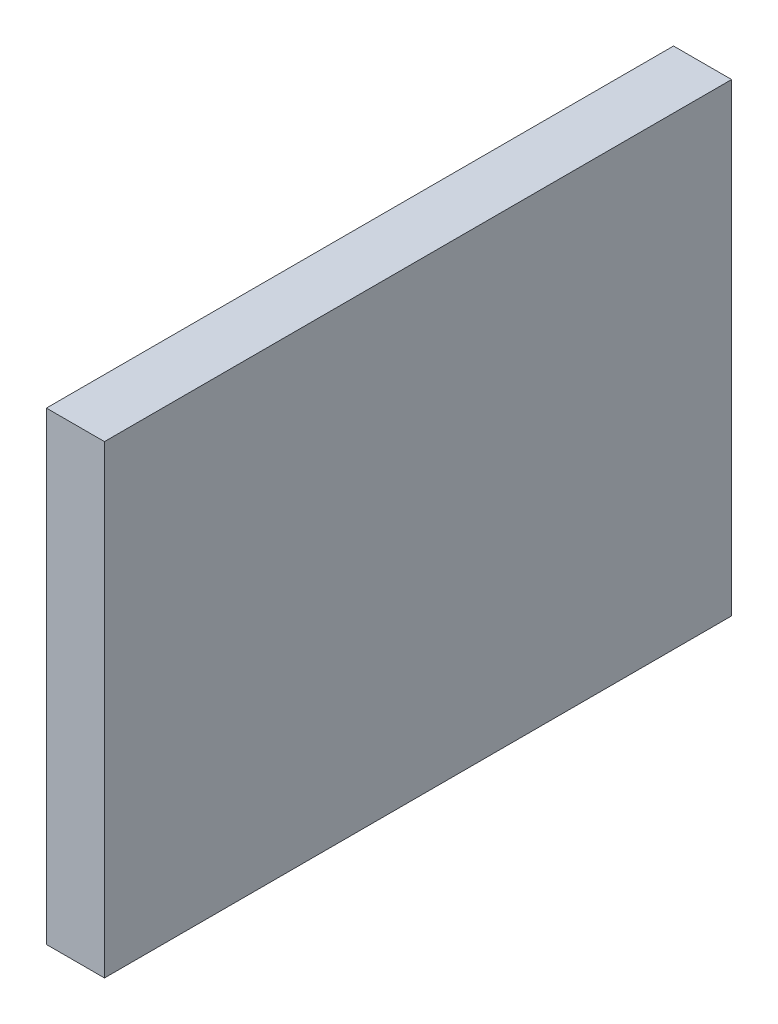
SolidWorks part; units mm, degrees
ref_plane "Front Plane" through (0, 0, 0) normal (0, 0, 1) x (1, 0, 0)
ref_plane "Top Plane" through (0, 0, 0) normal (0, 1, 0) x (1, 0, 0)
ref_plane "Right Plane" through (0, 0, 0) normal (1, 0, 0) x (0, 0, -1)
sketch "Sketch1" plane through (0, 0, 0) normal (1, 0, 0) x (0, 0, -1)
  line L1 (-34.29, 25.4) -> (34.29, 25.4)
  line L2 (-34.29, 25.4) -> (-34.29, -25.4)
  line L3 (-34.29, -25.4) -> (34.29, -25.4)
  line L4 (34.29, 25.4) -> (34.29, -25.4)
  point P4 (0, 25.4)
  point P6 (-34.29, 0)
  dimension "D1" = 68.58
  dimension "D2" = 50.8
extrude "Boss-Extrude1" add sketch "Sketch1" along normal blind 6.35
